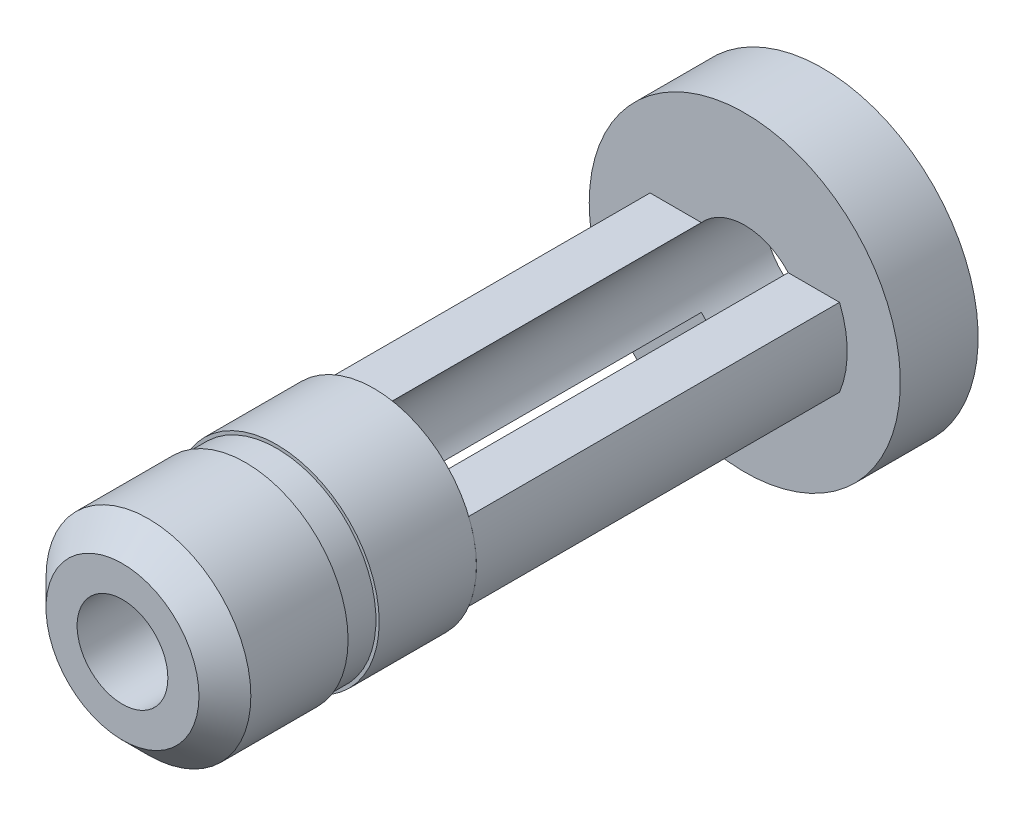
SolidWorks part; units mm, degrees
material "ASTM A36 Steel"
ref_plane "Front Plane" through (0, 0, 0) normal (0, 0, 1) x (1, 0, 0)
ref_plane "Top Plane" through (0, 0, 0) normal (0, 1, 0) x (1, 0, 0)
ref_plane "Right Plane" through (0, 0, 0) normal (1, 0, 0) x (0, 0, -1)
sketch "Sketch1" plane through (0, 0, 0) normal (0, 0, 1) x (1, 0, 0)
  circle A0 centre (0, 0) radius 7.9
  circle A1 centre (0, 0) radius 3.5
  dimension "D1" = 15.8
  dimension "D2" = 7
extrude "Boss-Extrude1" add sketch "Sketch1" along normal blind 19.4
chamfer "Chamfer1" distance 2 angle 45 1 edges at (7.9, 0, 19.4)
ref_plane "Plane7" [suppressed] through (0, 0, 7.5) normal (0, 0, -1) x (-1, 0, 0)
ref_plane "Plane8" through (0, 0, 9.9) normal (0, 0, -1) x (-1, 0, 0)
sketch "Sketch19" plane through (0, 0, 9.9) normal (0, 0, -1) x (-1, 0, 0)
  circle A0 centre (0, 0) radius 7.65
  circle A1 centre (0, 0) radius 7.9
  dimension "D1" = 15.3
extrude "Cut-Extrude6" cut sketch "Sketch19" along normal blind 2.4
sketch "Sketch20" plane through (0, 0, 0) normal (0, 0, -1) x (-1, 0, 0)
  circle A0 centre (0, 0) radius 7.9
  circle A1 centre (0, 0) radius 4.5
  dimension "D1" = 9
extrude "Boss-Extrude3" add sketch "Sketch20" along normal blind 28.6 separate body
sketch "Sketch21" plane through (0, 0, -28.6) normal (0, 0, -1) x (-1, 0, 0)
  line L1 (0, 3.0042) -> (-7.3065, 3.0042)
  line L9 (-7.3081, -3.0004) -> (0, -3.0004)
  line L12 (0, -3.0004) -> (7.3081, -3.0004)
  line L13 (0, 3.0042) -> (7.3065, 3.0042)
  circle A0 centre (0, 0) radius 7.9 construction
  arc A1 (-7.3065, 3.0042) -> (7.3065, 3.0042) centre (0, 0) cw
  arc A2 (-7.3081, -3.0004) -> (7.3081, -3.0004) centre (0, 0) ccw
extrude "Cut-Extrude7" cut sketch "Sketch21" against normal blind 28.6
ref_plane "Plane9" through (0, 0, -28.6) normal (0, 0, -1) x (-1, 0, 0)
sketch "Sketch22" plane through (0, 0, -28.6) normal (0, 0, -1) x (-1, 0, 0)
  circle A0 centre (0, 0) radius 12
  dimension "D1" = 24
extrude "Boss-Extrude4" add sketch "Sketch22" along normal blind 6
sketch "Sketch23" plane through (0, 0, -34.6) normal (0, 0, -1) x (-1, 0, 0)
  circle A0 centre (0, 0) radius 4.5
  dimension "D1" = 9
extrude "Cut-Extrude8" cut sketch "Sketch23" against normal up to next
